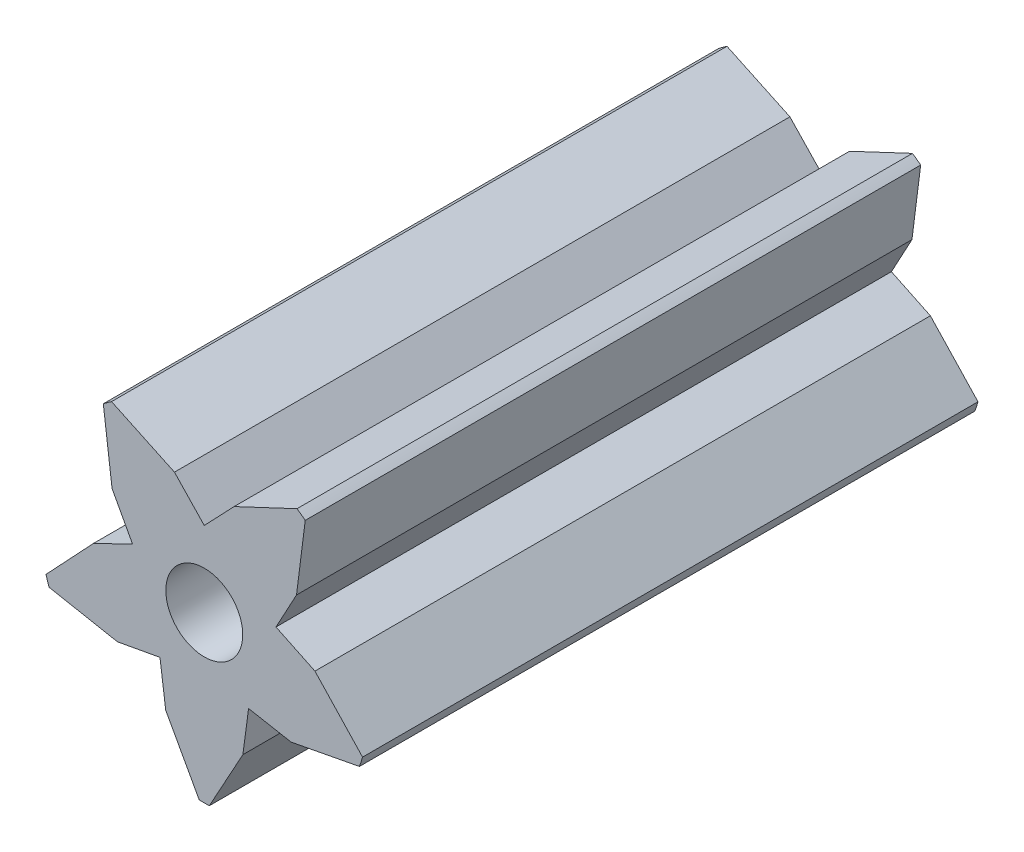
SolidWorks part; units mm, degrees
ref_plane "Front Plane" through (0, 0, 0) normal (0, 0, 1) x (1, 0, 0)
ref_plane "Top Plane" through (0, 0, 0) normal (0, 1, 0) x (1, 0, 0)
ref_plane "Right Plane" through (0, 0, 0) normal (1, 0, 0) x (0, 0, -1)
sketch "Sketch1" plane through (0, 0, 0) normal (0, 0, 1) x (1, 0, 0)
  line L1 (1.2374, -1.2374) -> (-1.2374, -1.2374) construction
  line L2 (1.2374, -1.2374) -> (1.2374, 1.2374) construction
  line L3 (1.2374, 1.2374) -> (-1.2374, 1.2374) construction
  line L4 (-1.2374, -1.2374) -> (-1.2374, 1.2374) construction
  line L5 (1.2374, -1.2374) -> (-1.2374, 1.2374) construction
  line L6 (1.2374, 1.2374) -> (-1.2374, -1.2374) construction
  circle A0 centre (0, 0) radius 7.5
  circle A1 centre (0, 0) radius 1.75
  dimension "D1" = 15
  dimension "D2" = 3.5
extrude "Boss-Extrude1" add sketch "Sketch1" along normal blind 28
sketch "Sketch2" plane through (0, 0, 0) normal (0, 0, 1) x (1, 0, 0)
  line L0 (0, 0) -> (0, 10.088) construction
  line L1 (0, 3.4293) -> (-1.3565, 4.8529)
  line L2 (-1.3565, 4.8529) -> (-4.2191, 6.2007)
  line L3 (-4.2191, 6.2007) -> (0, 11.2516)
  line L4 (4.2191, 6.2007) -> (0, 11.2516)
  line L5 (1.3565, 4.8529) -> (4.2191, 6.2007)
  line L6 (0, 3.4293) -> (1.3565, 4.8529)
  circle A14 centre (0, 0) radius 7.5 construction
  point P16 (0, 7.5)
extrude "Cut-Extrude1" cut sketch "Sketch2" along normal through all
pattern_circular "CirPattern1" count 5 over 360 about axis through (0, 0, 0) along (0, 0, 1) of "Cut-Extrude1"
sketch "Sketch3" plane through (0, 0, 0) normal (0, 0, 1) x (1, 0, 0)
  circle A0 centre (0, 0) radius 7.5
  dimension "D1" = 15
